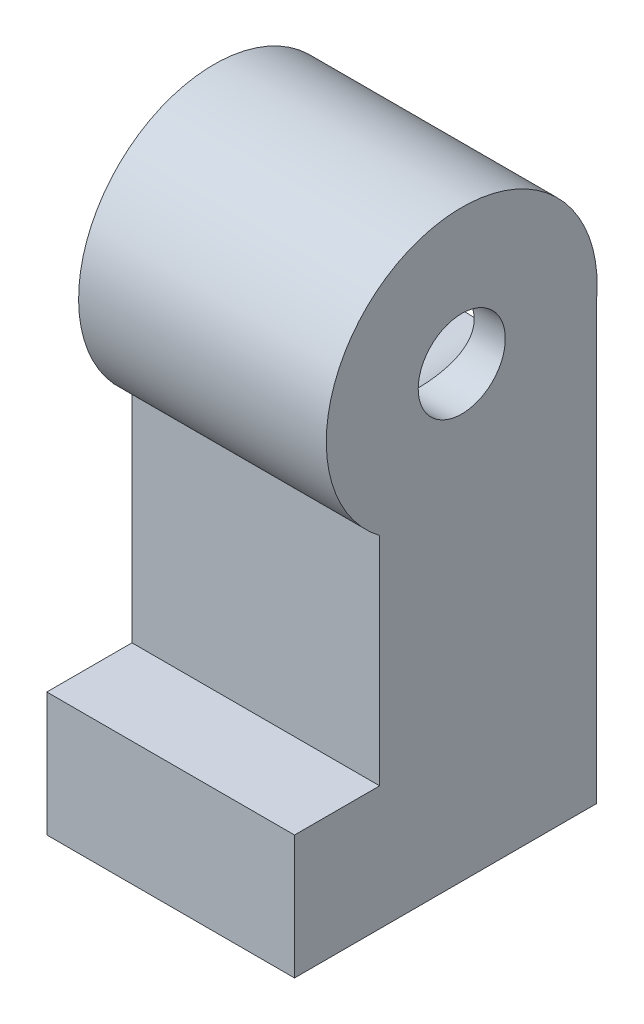
SolidWorks part; units mm, degrees
ref_plane "Front Plane" through (0, 0, 0) normal (0, 0, 1) x (1, 0, 0)
ref_plane "Top Plane" through (0, 0, 0) normal (0, 1, 0) x (1, 0, 0)
ref_plane "Right Plane" through (0, 0, 0) normal (1, 0, 0) x (0, 0, -1)
sketch "Sketch1" plane through (0, 0, 0) normal (1, 0, 0) x (0, 0, -1)
  line L0 (0, 0) -> (7.8, 0)
  line L1 (7.8, 0) -> (7.8, 3.2)
  line L2 (7.8, 3.2) -> (5.6, 3.2)
  line L3 (5.6, 3.2) -> (5.6, 8.8)
  line L4 (0, 11.2) -> (0, 0)
  arc A1 (5.6, 8.8) -> (0, 11.2) centre (3.4789, 11.584) ccw
  dimension "D4" = 5.6
  dimension "D5" = 7
  dimension "D6" = 2.2
  dimension "D1" = 7.8
  dimension "D2" = 11.2
  dimension "D3" = 3.2
extrude "Boss-Extrude1" add sketch "Sketch1" along normal blind 6.4
sketch "Sketch2" plane through (6.4, 0, 0) normal (1, 0, 0) x (0, 0, -1)
  circle A0 centre (3.4789, 11.584) radius 1.125
  dimension "D1" = 2.25
extrude "Cut-Extrude1" cut sketch "Sketch2" against normal blind 2
sketch "Sketch4" plane through (0, 0, 0) normal (0, 0, 1) x (1, 0, 0)
  line L0 (6.4, 0) -> (0, 0) construction
  circle A0 centre (3.2, 11.7) radius 2.4
  point P4 (3.2, 0)
  dimension "D1" = 4.8
  dimension "D2" = 11.7
extrude "Cut-Extrude3" cut sketch "Sketch4" against normal mid plane 10
sketch "Sketch5" plane through (0, 0, 0) normal (0, -1, 0) x (1, 0, 0)
  line L0 (6.4, 0) -> (0, 0) construction
  line L1 (5.6, -1.4) -> (0.8, -1.4)
  line L2 (5.6, -1.4) -> (5.6, -4.7)
  line L3 (5.6, -4.7) -> (0.8, -4.7)
  line L4 (0.8, -1.4) -> (0.8, -4.7)
  line L5 (5.6, -1.4) -> (0.8, -4.7) construction
  line L6 (5.6, -4.7) -> (0.8, -1.4) construction
  line L7 (0, 0) -> (0, -7.8) construction
  line L8 (6.4, 0) -> (6.4, -7.8) construction
  point P0 (3.2, -3.05)
  dimension "D1" = 3.3
  dimension "D2" = 4.8
  dimension "D3" = 1.4
  dimension "D4" = 0.8
  dimension "D5" = 0.8
extrude "Cut-Extrude4" cut sketch "Sketch5" against normal blind 8.9
ref_plane "Plane1" through (0, 0, 10) normal (0, 0, 1) x (1, 0, 0)
mirror "Mirror1" [suppressed] about plane through (0, 0, 10) normal (0, 0, 1)
pattern_linear "LPattern1" [suppressed] count 2 spacing 50
mirror "Mirror4" about plane through (0, 0, 10) normal (0, 0, 1) of bodies 105
other "Intersect1"
delete or keep bodies "Body-Delete/Keep 1" type delete bodies bodies 116
